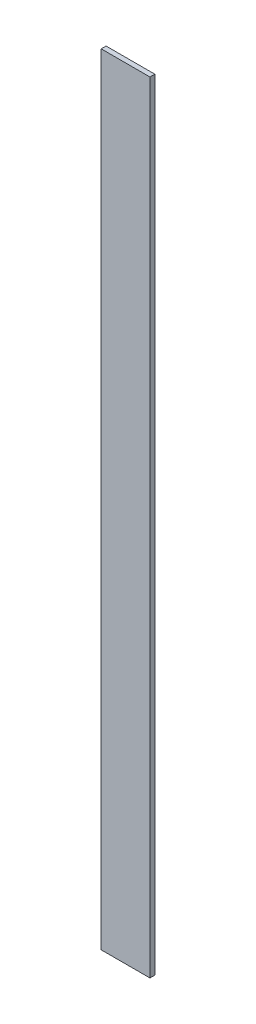
SolidWorks part; units mm, degrees
material "AISI 1020 Steel, Cold Rolled"
ref_plane "Front Plane" through (0, 0, 0) normal (0, 0, 1) x (1, 0, 0)
ref_plane "Top Plane" through (0, 0, 0) normal (0, 1, 0) x (1, 0, 0)
ref_plane "Right Plane" through (0, 0, 0) normal (1, 0, 0) x (0, 0, -1)
sketch "Sketch1" plane through (0, 0, 0) normal (0, 1, 0) x (1, 0, 0)
  line L1 (-6.35, -0.635) -> (6.35, -0.635)
  line L2 (-6.35, -0.635) -> (-6.35, 0.635)
  line L3 (-6.35, 0.635) -> (6.35, 0.635)
  line L4 (6.35, -0.635) -> (6.35, 0.635)
  line L5 (-6.35, -0.635) -> (6.35, 0.635) construction
  line L6 (-6.35, 0.635) -> (6.35, -0.635) construction
  point P0 (0, 0)
  dimension "D1" = 1.27
  dimension "D2" = 12.7
extrude "Boss-Extrude1" add sketch "Sketch1" along normal blind 203.2
